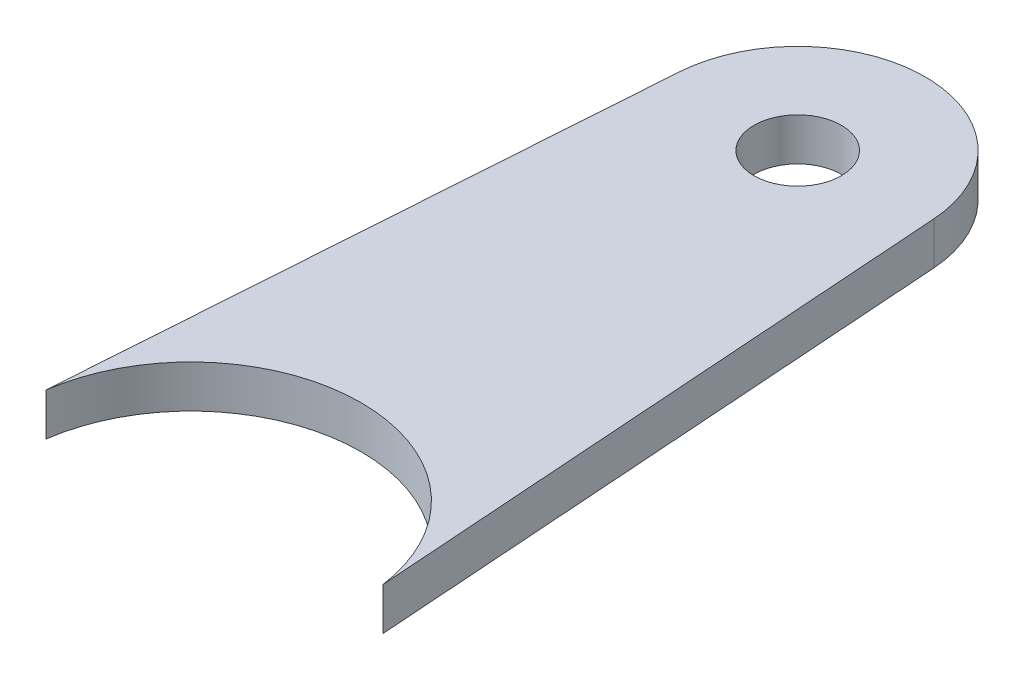
SolidWorks part; units mm, degrees
ref_plane "Front Plane" through (0, 0, 0) normal (0, 0, 1) x (1, 0, 0)
ref_plane "Top Plane" through (0, 0, 0) normal (0, 1, 0) x (1, 0, 0)
ref_plane "Right Plane" through (0, 0, 0) normal (1, 0, 0) x (0, 0, -1)
sketch "Sketch1" plane through (0, 0, 0) normal (0, 1, 0) x (1, 0, 0)
  line L0 (0, 0) -> (3.198, 45.9645)
  line L1 (0, 0) -> (25.4, 0)
  line L2 (25.4, 0) -> (22.202, 45.9645)
  line L3 (12.7, 42.0395) -> (12.7, 0) construction
  arc A1 (3.198, 45.9645) -> (22.202, 45.9645) centre (12.7, 45.3034) cw
  circle A2 centre (12.7, 45.3034) radius 3.2639
  circle A3 centre (12.7, 0) radius 12.7
  point P9 (12.7, 0)
  dimension "D1" = 6.5278
  dimension "D2" = 45.3034
  dimension "D3" = 9.525
  dimension "D5" = 25.4
  dimension "D4" = 25.4
extrude "Boss-Extrude1" add sketch "Sketch1" along normal blind 3.175 contours A3 L2 A1 L0 A2
